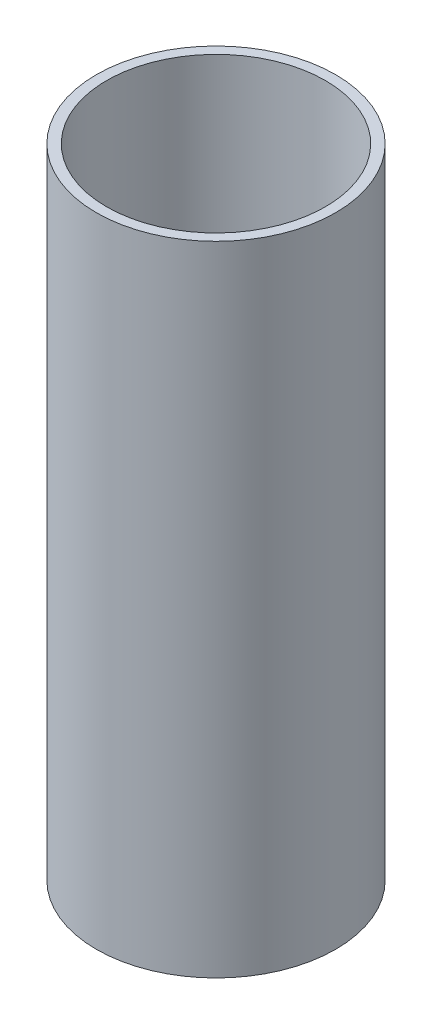
SolidWorks part; units mm, degrees
material "Free-Cutting Brass, UNS C36000"
ref_plane "Front Plane" through (0, 0, 0) normal (0, 0, 1) x (1, 0, 0)
ref_plane "Top Plane" through (0, 0, 0) normal (0, 1, 0) x (1, 0, 0)
ref_plane "Right Plane" through (0, 0, 0) normal (1, 0, 0) x (0, 0, -1)
sketch "Sketch1" plane through (0, 0, 0) normal (0, 1, 0) x (1, 0, 0)
  circle A0 centre (0, 0) radius 9.525
  dimension "D1" = 19.05
extrude "Boss-Extrude1" add sketch "Sketch1" along normal blind 50.8
sketch "Sketch2" plane through (0, 50.8, 0) normal (0, 1, 0) x (1, 0, 0)
  circle A0 centre (0, 0) radius 8.7122
  dimension "D1" = 17.4244
extrude "Cut-Extrude1" cut sketch "Sketch2" against normal through all
